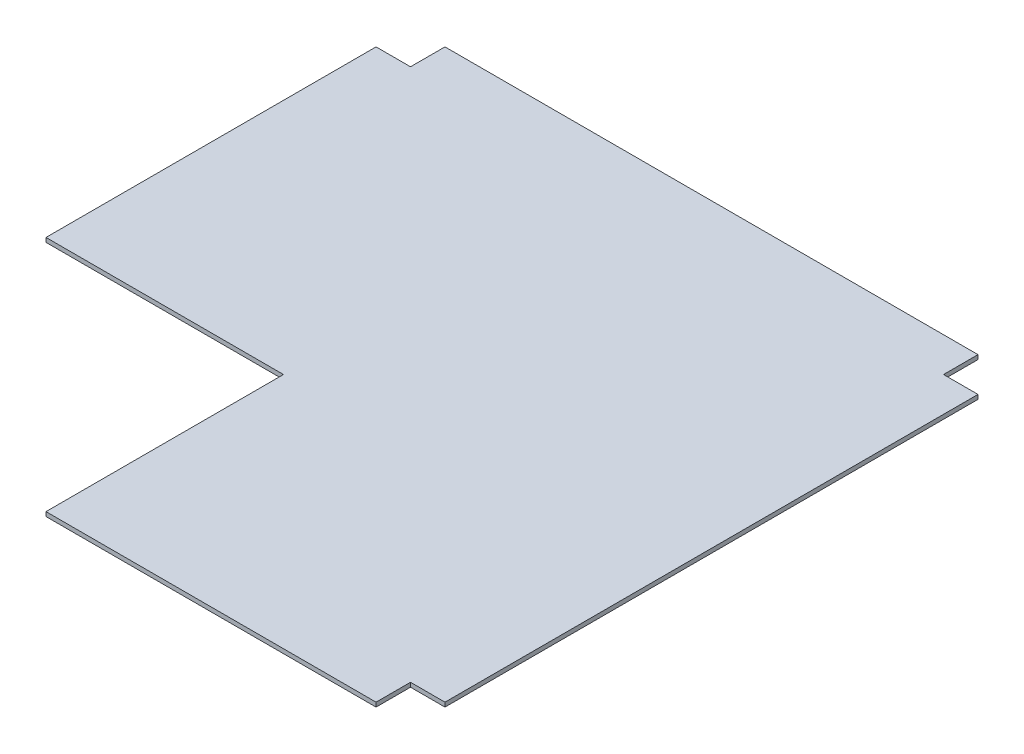
SolidWorks part; units mm, degrees
ref_plane "Front Plane" through (0, 0, 0) normal (0, 0, 1) x (1, 0, 0)
ref_plane "Top Plane" through (0, 0, 0) normal (0, 1, 0) x (1, 0, 0)
ref_plane "Right Plane" through (0, 0, 0) normal (1, 0, 0) x (0, 0, -1)
sketch "Sketch1" plane through (0, 0, 0) normal (0, 1, 0) x (1, 0, 0)
  line L1 (0, 0) -> (443.65, 0)
  line L2 (0, 0) -> (0, 443.65)
  line L3 (0, 443.65) -> (443.65, 443.65)
  line L4 (443.65, 0) -> (443.65, 443.65)
  line L5 (0, 0) -> (25.4, 0)
  line L6 (0, 0) -> (0, 25.4)
  line L7 (0, 25.4) -> (25.4, 25.4)
  line L8 (25.4, 0) -> (25.4, 25.4)
  line L9 (0, 443.65) -> (25.4, 443.65)
  line L10 (0, 443.65) -> (0, 418.25)
  line L11 (0, 418.25) -> (25.4, 418.25)
  line L12 (25.4, 443.65) -> (25.4, 418.25)
  line L13 (443.65, 443.65) -> (418.25, 443.65)
  line L14 (443.65, 443.65) -> (443.65, 418.25)
  line L15 (443.65, 418.25) -> (418.25, 418.25)
  line L16 (418.25, 443.65) -> (418.25, 418.25)
  line L17 (443.65, 0) -> (418.25, 0)
  line L18 (443.65, 0) -> (443.65, 25.4)
  line L19 (443.65, 25.4) -> (418.25, 25.4)
  line L20 (418.25, 0) -> (418.25, 25.4)
  line L21 (0, 0) -> (175, 0)
  line L22 (0, 0) -> (0, 175)
  line L23 (0, 175) -> (175, 175)
  line L24 (175, 0) -> (175, 175)
  dimension "D1" = 443.65
  dimension "D2" = 443.65
  dimension "D3" = 25.4
  dimension "D4" = 175
extrude "Boss-Extrude1" add sketch "Sketch1" along normal blind 3.175 contours L1 L20 L19 L4 L15 L16 L3 L12 L11 L2 L7 L8
